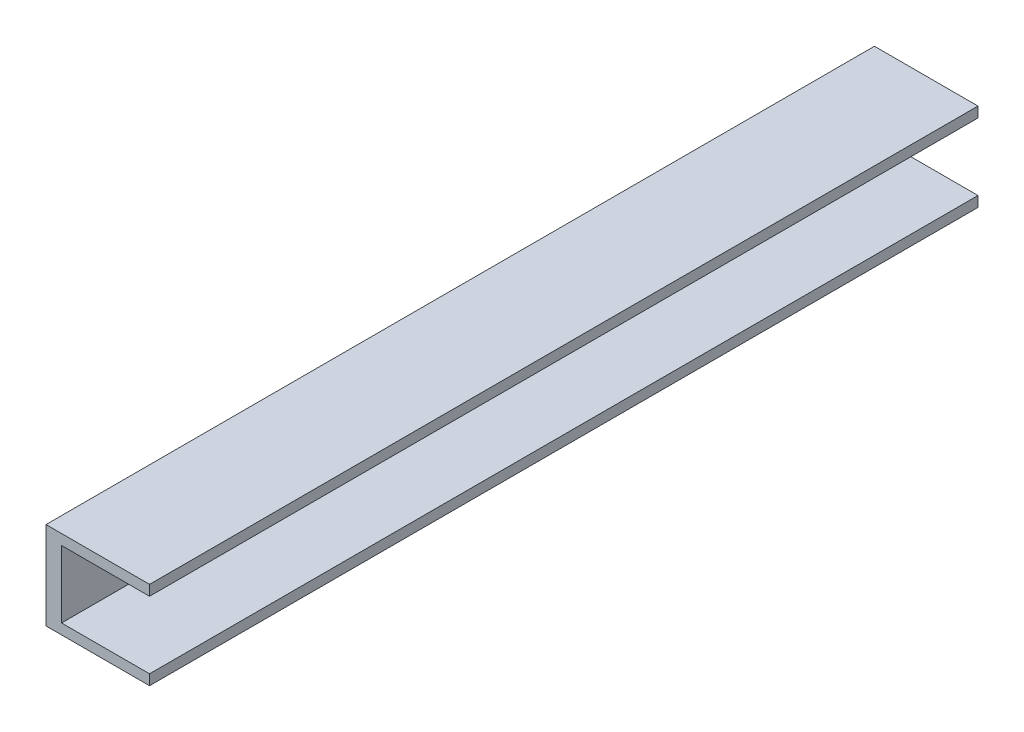
SolidWorks part; units mm, degrees
ref_plane "Plane1" through (0, 0, 0) normal (0, 0, 1) x (1, 0, 0)
ref_plane "Plane2" through (0, 0, 0) normal (0, 1, 0) x (1, 0, 0)
ref_plane "Plane3" through (0, 0, 0) normal (1, 0, 0) x (0, 0, -1)
sketch "Sketch1" plane through (0, 0, 0) normal (0, 0, 1) x (1, 0, 0)
  line L0 (0, 0) -> (0, 26.924)
  line L2 (4.7625, 23.7465) -> (4.7625, 3.1775)
  line L3 (4.765, 3.175) -> (31.75, 3.175)
  line L4 (31.75, 6.35) -> (31.75, 0) construction
  line L5 (31.75, 0) -> (0, 0)
  line L6 (31.75, 26.924) -> (0, 26.924)
  line L7 (31.75, 0) -> (31.75, 3.175)
  line L8 (31.75, 26.924) -> (31.75, 23.749)
  line L9 (4.765, 23.749) -> (31.75, 23.749)
  arc A0 (4.7625, 23.7465) -> (4.765, 23.749) centre (4.765, 23.7465) cw
  arc A2 (4.765, 3.175) -> (4.7625, 3.1775) centre (4.765, 3.1775) cw
  dimension "D1" = 3.175
  dimension "Thickness" = 3.175
  dimension "tw" = 4.7625
  dimension "V_Leg" = 26.924
extrude "BaseChannelse" add sketch "Sketch1" along normal mid plane 254
equation "\"D1@Sketch1\" = \"Thickness@Sketch1\""
